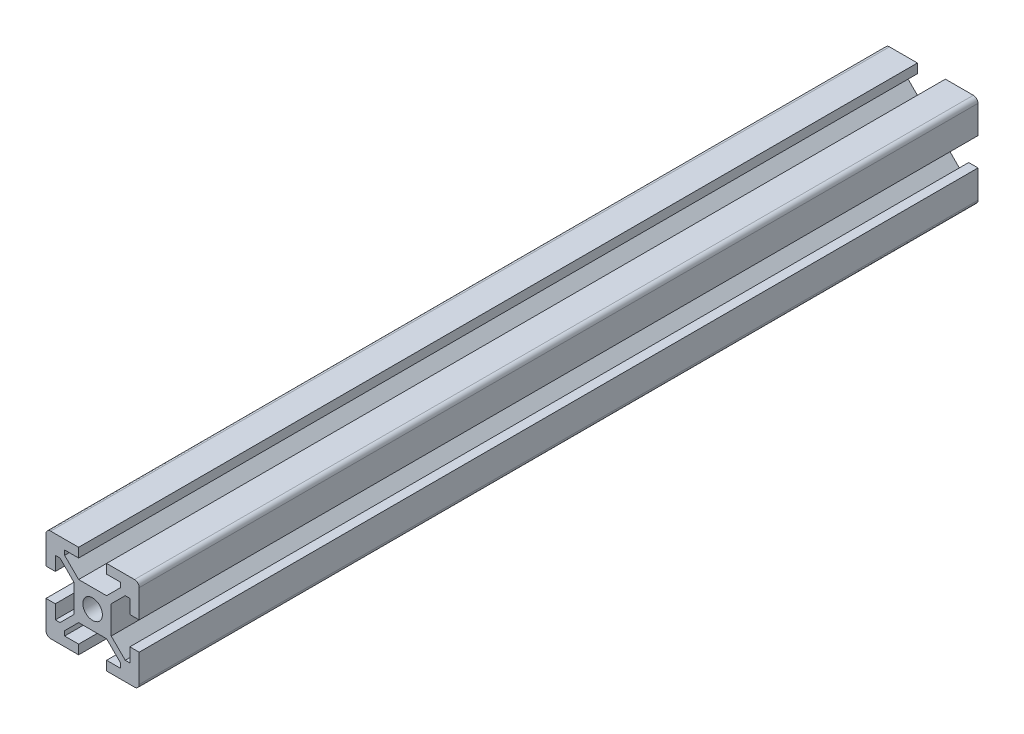
SolidWorks part; units mm, degrees
material "6061 Alloy"
ref_plane "Front Plane" through (0, 0, 0) normal (0, 0, 1) x (1, 0, 0)
ref_plane "Top Plane" through (0, 0, 0) normal (0, 1, 0) x (1, 0, 0)
ref_plane "Right Plane" through (0, 0, 0) normal (1, 0, 0) x (0, 0, -1)
ref_plane "Plane1" through (0, 0, 0) normal (0, 0, -1) x (-1, 0, 0)
sketch "Sketch1" plane through (0, 0, 0) normal (0, 0, -1) x (-1, 0, 0)
  line L0 (6, -8) -> (3, -8)
  line L1 (3, -8) -> (3, -10)
  line L2 (3, -10) -> (9, -10)
  line L3 (10, -9) -> (10, -3)
  line L4 (10, -3) -> (8, -3)
  line L5 (8, -3) -> (8, -6)
  line L6 (8, -6) -> (7, -6)
  line L7 (7, -6) -> (4, -3)
  line L8 (4, -3) -> (4, 3)
  line L9 (4, 3) -> (7, 6)
  line L10 (7, 6) -> (8, 6)
  line L11 (8, 6) -> (8, 3)
  line L12 (8, 3) -> (10, 3)
  line L13 (10, 3) -> (10, 9)
  line L14 (9, 10) -> (3, 10)
  line L15 (3, 10) -> (3, 8)
  line L16 (3, 8) -> (6, 8)
  line L17 (6, 8) -> (6, 7)
  line L18 (6, 7) -> (3, 4)
  line L19 (3, 4) -> (-3, 4)
  line L20 (-3, 4) -> (-6, 7)
  line L21 (-6, 7) -> (-6, 8)
  line L22 (-6, 8) -> (-3, 8)
  line L23 (-3, 8) -> (-3, 10)
  line L24 (-3, 10) -> (-9, 10)
  line L25 (-10, 9) -> (-10, 3)
  line L26 (-10, 3) -> (-8, 3)
  line L27 (-8, 3) -> (-8, 6)
  line L28 (-8, 6) -> (-7, 6)
  line L29 (-7, 6) -> (-4, 3)
  line L30 (-4, 3) -> (-4, -3)
  line L31 (-4, -3) -> (-7, -6)
  line L32 (-7, -6) -> (-8, -6)
  line L33 (-8, -6) -> (-8, -3)
  line L34 (-8, -3) -> (-10, -3)
  line L35 (-10, -3) -> (-10, -9)
  line L36 (-9, -10) -> (-3, -10)
  line L37 (-3, -10) -> (-3, -8)
  line L38 (-3, -8) -> (-6, -8)
  line L39 (-6, -8) -> (-6, -7)
  line L40 (-6, -7) -> (-3, -4)
  line L41 (-3, -4) -> (3, -4)
  line L42 (3, -4) -> (6, -7)
  line L43 (6, -7) -> (6, -8)
  line L44 (0, 4) -> (0, 0) construction
  line L45 (0, 0) -> (-4, 0) construction
  line L46 (0, 0) -> (4, 0) construction
  line L47 (0, 0) -> (0, -4) construction
  circle A0 centre (0, 0) radius 2.1
  arc A1 (9, -10) -> (10, -9) centre (9, -9) ccw
  arc A2 (10, 9) -> (9, 10) centre (9, 9) ccw
  arc A3 (-9, 10) -> (-10, 9) centre (-9, 9) ccw
  arc A4 (-10, -9) -> (-9, -10) centre (-9, -9) ccw
  dimension "D6" = 1
  dimension "D10" = 4.2
  dimension "D1" = 10
  dimension "D2" = 10
  dimension "D3" = 10
  dimension "D4" = 10
  dimension "D5" = 8
  dimension "D7" = 2
  dimension "D8" = 7
  dimension "D9" = 8
  dimension "D11" = 1
  dimension "D12" = 1
  dimension "D13" = 2
  dimension "D14" = 3
  dimension "D15" = 2
  dimension "D16" = 1
  dimension "D17" = 1
  dimension "D18" = 4.2426
  dimension "D19" = 6
  dimension "D20" = 7
extrude "Boss-Extrude1" add sketch "Sketch1" against normal blind 180
ref_plane "Plane2" through (0, 0, 0) normal (1, 0, 0) x (0, 0, -1)
sketch "Sketch2" plane through (0, 10, 0) normal (0, 1, 0) x (1, 0, 0)
  line L0 (0, -3.3) -> (0, 3.3) construction
  line L1 (0, -175.9786) -> (0, -162.307) construction
  circle A0 centre (0, -175.9786) radius 3
